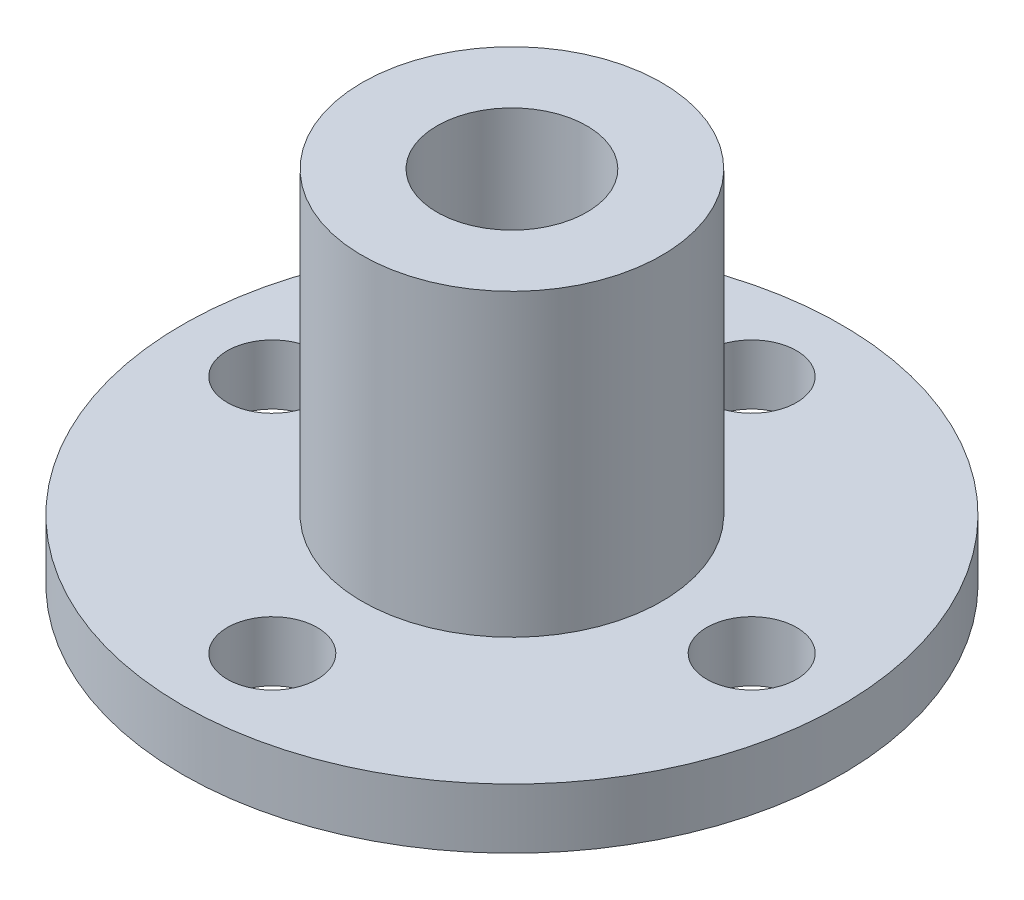
SolidWorks part; units mm, degrees
ref_plane "前视基准面" through (0, 0, 0) normal (0, 0, 1) x (1, 0, 0)
ref_plane "上视基准面" through (0, 0, 0) normal (0, 1, 0) x (1, 0, 0)
ref_plane "右视基准面" through (0, 0, 0) normal (1, 0, 0) x (0, 0, -1)
sketch "草图1" plane through (0, 0, 0) normal (0, 1, 0) x (0, 0, -1)
  circle A0 centre (0, 0) radius 11
  point P3 (0, 0)
  point P4 (0, 0)
  dimension "D1" = 22
extrude "凸台-拉伸1" add sketch "草图1" along normal blind 2
sketch "草图2" plane through (0, 2, 0) normal (0, 1, 0) x (0, 0, -1)
  circle A0 centre (0, 0) radius 5
  circle A1 centre (0, 0) radius 5
  dimension "D1" = 10
extrude "凸台-拉伸2" add sketch "草图2" along normal blind 10
sketch "草图3" plane through (0, 2, 0) normal (0, 1, 0) x (0, 0, -1)
  circle A0 centre (0, 0) radius 8 construction
  circle A1 centre (0, 8) radius 1.5
  circle A2 centre (0.001, 0.001) radius 8 construction
  circle A3 centre (8.001, 0.001) radius 1.5
  circle A4 centre (0.002, 0) radius 8 construction
  circle A5 centre (0.002, -8) radius 1.5
  circle A6 centre (0.001, -0.001) radius 8 construction
  circle A7 centre (-7.999, -0.001) radius 1.5
  point P20 (0.001, 0)
  dimension "D1" = 3
  dimension "D2" = 4
extrude "切除-拉伸1" cut sketch "草图3" against normal blind 10
sketch "草图5" plane through (0, 12, 0) normal (0, 1, 0) x (1, 0, 0)
  circle A0 centre (0, 0) radius 2.5
  dimension "D1" = 5
extrude "切除-拉伸2" cut sketch "草图5" against normal through all
